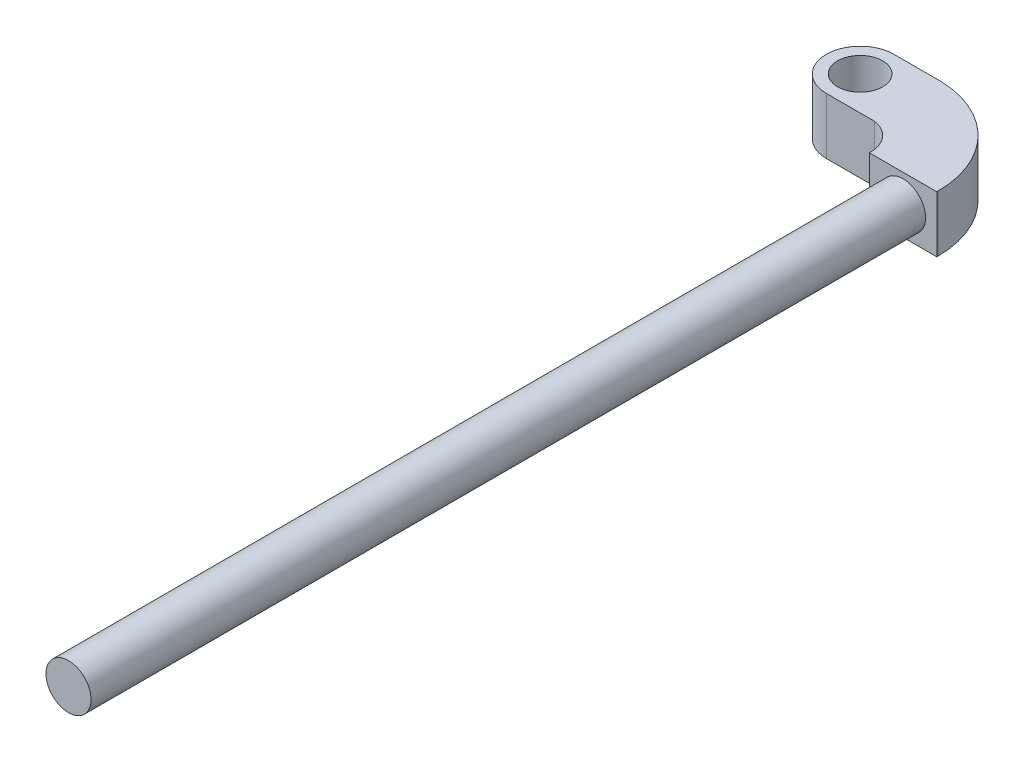
SolidWorks part; units mm, degrees
material "天然橡胶"
ref_plane "前视基准面" through (0, 0, 0) normal (0, 0, 1) x (1, 0, 0)
ref_plane "上视基准面" through (0, 0, 0) normal (0, 1, 0) x (1, 0, 0)
ref_plane "右视基准面" through (0, 0, 0) normal (1, 0, 0) x (0, 0, -1)
sketch "草图2" plane through (0, 0, 0) normal (0, 1, 0) x (1, 0, 0)
  line L0 (-3.9323, 0) -> (4.6079, 0) construction
  line L1 (-3.9323, 3) -> (0.3378, 3)
  line L2 (-3.9323, -3) -> (0.3378, -3)
  line L4 (0.3378, 3) -> (0.3378, -3)
  arc A0 (-3.9323, 3) -> (-3.9323, -3) centre (-3.9323, 0) ccw
  circle A2 centre (-3.9323, 0) radius 2
  point P3 (0.3378, 0)
  dimension "D1" = 6
extrude "凸台-拉伸2" add sketch "草图2" along normal blind 5
sketch "草图3" plane through (0, 0, 0) normal (0, 1, 0) x (1, 0, 0)
  line L0 (2.5377, -79.6558) -> (8.5207, -79.6558)
  line L4 (2.5377, -5.5253) -> (2.5377, -8.4297)
  line L5 (8.5207, -5.5253) -> (8.5207, -8.4297)
  line L6 (5.5292, -8.4297) -> (5.5292, -79.8808) construction
  line L7 (5.5292, -3) -> (5.5292, -16.2372) construction
  line L8 (8.5207, -8.4297) -> (8.5207, -79.6558)
  line L9 (2.5377, -8.4297) -> (2.5377, -79.6558)
  line L10 (0.3378, 3) -> (0.3378, -3)
  arc A0 (0.3378, 3) -> (8.5207, -5.5253) centre (-0.0117, -5.5253) cw
  arc A1 (0.3378, -3) -> (2.5377, -5.5253) centre (-0.0117, -5.5253) cw
  point P19 (5.8401, -11.6899)
extrude "凸台-拉伸3" add sketch "草图3" along normal blind 5
sketch "草图4" plane through (0, 0, 79.6558) normal (0, 0, 1) x (1, 0, 0)
  line L0 (5.5292, 5) -> (5.5292, 0) construction
  line L1 (2.5377, 5) -> (8.5207, 5) construction
  line L2 (2.5377, 0) -> (8.5207, 0) construction
  circle A0 centre (5.5292, 2.5) radius 2
extrude "切除-拉伸1" cut sketch "草图4" against normal blind 74 flip side to cut
sketch "草图6" plane through (0, 0, 79.6558) normal (0, 0, 1) x (1, 0, 0)
  point P0 (5.6643, 2.3745)
